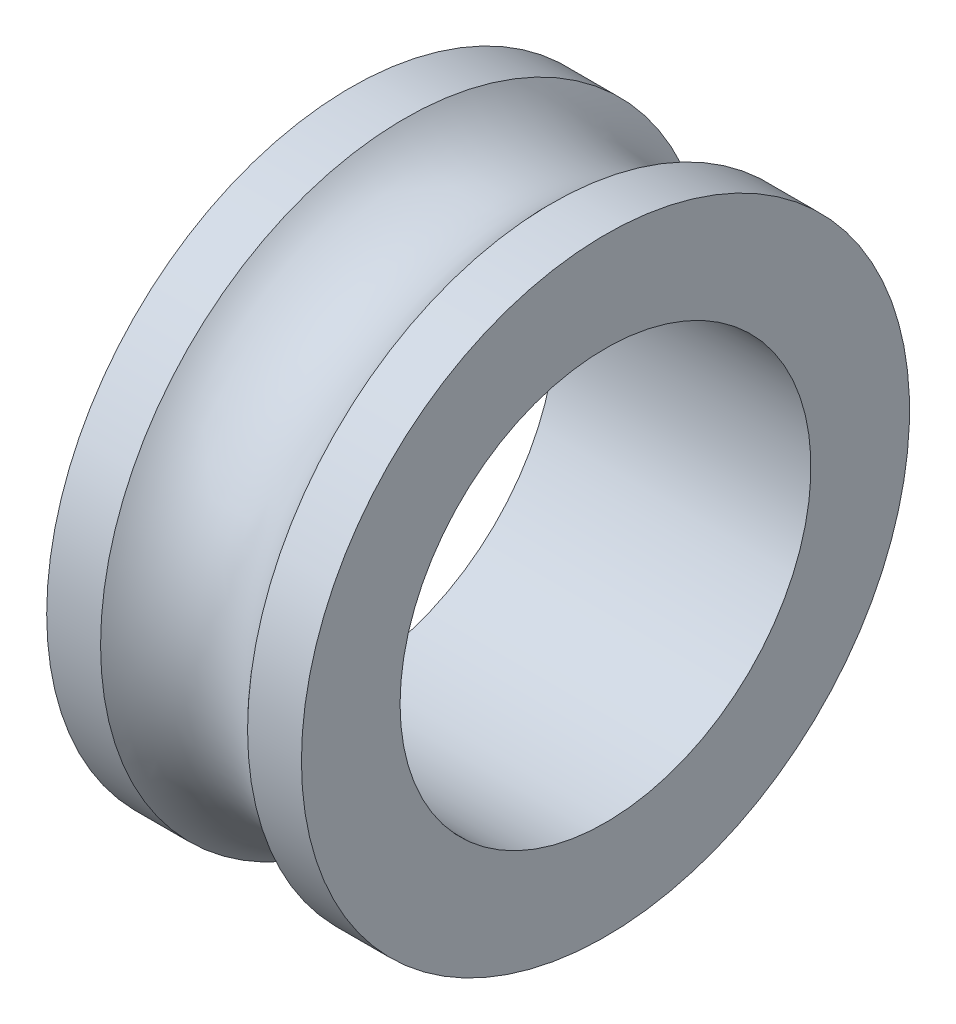
SolidWorks part; units mm, degrees
ref_plane "Front Plane" through (0, 0, 0) normal (0, 0, 1) x (1, 0, 0)
ref_plane "Top Plane" through (0, 0, 0) normal (0, 1, 0) x (1, 0, 0)
ref_plane "Right Plane" through (0, 0, 0) normal (1, 0, 0) x (0, 0, -1)
sketch "Sketch1" plane through (0, 0, 0) normal (0, 0, 1) x (1, 0, 0)
  line L0 (-15.5, 0) -> (32.1123, 0) construction
  line L1 (-15.5, 37) -> (-8.9443, 37)
  line L2 (15.5, 37) -> (8.9443, 37)
  line L3 (15.5, 37) -> (15.5, 25)
  line L4 (15.5, 25) -> (-15.5, 25)
  line L5 (-15.5, 37) -> (-15.5, 25)
  line L6 (15.5, 37) -> (-15.5, 25) construction
  line L7 (15.5, 25) -> (-15.5, 37) construction
  arc A0 (-8.9443, 37) -> (8.9443, 37) centre (0, 45) ccw
  point P3 (0, 31)
  dimension "D5" = 12
  dimension "D1" = 31
  dimension "D2" = 25
  dimension "D3" = 37
  dimension "D4" = 8
revolve "Revolve1" add sketch "Sketch1" angle 360 about L0
